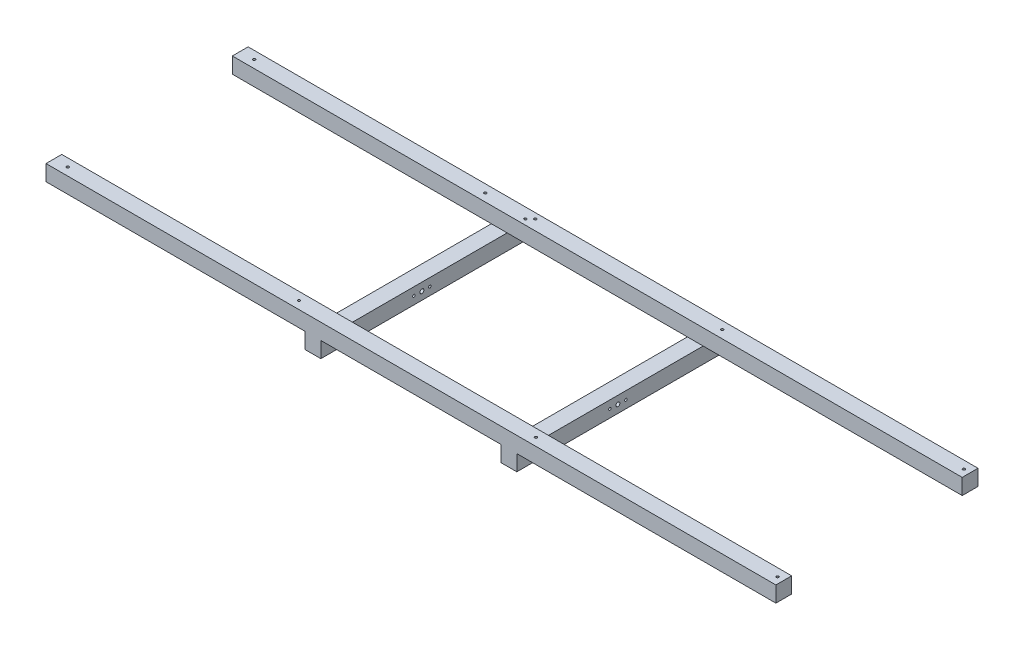
SolidWorks part; units mm, degrees
ref_plane "Plano frontal" through (0, 0, 0) normal (0, 0, 1) x (1, 0, 0)
ref_plane "Plano superior" through (0, 0, 0) normal (0, 1, 0) x (1, 0, 0)
ref_plane "Plano direito" through (0, 0, 0) normal (1, 0, 0) x (0, 0, -1)
sketch "Esboço1" plane through (0, 0, 0) normal (0, 1, 0) x (1, 0, 0)
  line L1 (-212.55, 202.85) -> (-180.85, 202.85)
  line L2 (-212.55, 202.85) -> (-212.55, -202.85)
  line L3 (-212.55, -202.85) -> (-180.85, -202.85)
  line L4 (-180.85, 202.85) -> (-180.85, -202.85)
  line L5 (180.85, 202.85) -> (212.55, 202.85)
  line L6 (180.85, 202.85) -> (180.85, -202.85)
  line L7 (180.85, -202.85) -> (212.55, -202.85)
  line L8 (212.55, 202.85) -> (212.55, -202.85)
  dimension "D1" = 405.7
  dimension "D2" = 31.7
  dimension "D3" = 31.7
  dimension "D4" = 405.7
  dimension "D5" = 361.7
extrude "Ressalto-extrusão1" add sketch "Esboço1" against normal blind 31.7
sketch "Esboço3" plane through (0, 0, 0) normal (0, 1, 0) x (1, 0, 0)
  line L0 (-212.55, 202.85) -> (-212.55, -202.85) construction
  line L1 (-732.55, 202.85) -> (732.55, 202.85)
  line L2 (-732.55, 202.85) -> (-732.55, 171.15)
  line L3 (-732.55, 171.15) -> (732.55, 171.15)
  line L4 (732.55, 202.85) -> (732.55, 171.15)
  line L5 (-732.55, -202.85) -> (732.55, -202.85)
  line L6 (-732.55, -202.85) -> (-732.55, -171.15)
  line L7 (-732.55, -171.15) -> (732.55, -171.15)
  line L8 (732.55, -202.85) -> (732.55, -171.15)
  line L9 (212.55, -202.85) -> (212.55, 202.85) construction
  dimension "D1" = 1465.1
  dimension "D2" = 520
  dimension "D3" = 405.7
  dimension "D4" = 31.7
  dimension "D5" = 31.7
  dimension "D6" = 520
extrude "Ressalto-extrusão2" add sketch "Esboço3" along normal blind 31.7
sketch "Esboço4" plane through (0, 0, 0) normal (0, 1, 0) x (1, 0, 0)
  line L0 (732.55, 171.15) -> (732.55, 202.85) construction
  line L1 (732.55, -202.85) -> (732.55, -171.15) construction
  line L2 (-732.55, -171.15) -> (-732.55, -202.85) construction
  line L3 (-732.55, 202.85) -> (-732.55, 171.15) construction
  line L4 (-732.55, 171.15) -> (732.55, 171.15) construction
  line L5 (732.55, -171.15) -> (-732.55, -171.15) construction
  line L6 (-732.55, -202.85) -> (732.55, -202.85) construction
  line L7 (732.55, 202.85) -> (-732.55, 202.85) construction
  line L8 (-180.85, -171.15) -> (-180.85, 171.15) construction
  circle A0 centre (720, 187) radius 2.5
  circle A1 centre (720, -187) radius 2.5
  circle A2 centre (235.05, 187) radius 2.5
  circle A3 centre (235.05, -187) radius 2.5
  circle A4 centre (-704.55, 187) radius 2.5
  circle A5 centre (-704.55, -187) radius 2.5
  circle A6 centre (-240.55, 187) radius 2.5
  circle A7 centre (-240.55, -187) radius 2.5
  circle A10 centre (-155, 182) radius 2.5
  circle A11 centre (-145, 192) radius 2.5
  point P24 (0, 0)
  point P26 (-155.2024, 184.0108)
  dimension "D1" = 5
  dimension "D6" = 5
  dimension "D15" = 10
  dimension "D19" = 5
  dimension "D2" = 12.55
  dimension "D3" = 484.95
  dimension "D4" = 12.55
  dimension "D5" = 484.95
  dimension "D7" = 28
  dimension "D8" = 464
  dimension "D9" = 28
  dimension "D10" = 464
  dimension "D11" = 15.85
  dimension "D12" = 15.85
  dimension "D13" = 15.85
  dimension "D14" = 15.85
  dimension "D16" = 10
  dimension "D17" = 10.85
  dimension "D18" = 25.85
extrude "Corte-extrusão2" cut sketch "Esboço4" along normal blind 31.7
sketch "Esboço5" plane through (0, 0, 0) normal (1, 0, 0) x (0, 0, -1)
  line L0 (-171.15, 0) -> (171.15, 0) construction
  line L1 (-202.85, -31.7) -> (-202.85, 0) construction
  circle A0 centre (16, -15.85) radius 2.5
  circle A1 centre (-16, -15.85) radius 2.5
  circle A2 centre (0, -15.85) radius 4
  dimension "D1" = 8
  dimension "D2" = 5
  dimension "D3" = 5
  dimension "D4" = 15.85
  dimension "D5" = 202.85
  dimension "D6" = 32
  dimension "D7" = 16
extrude "Corte-extrusão3" cut sketch "Esboço5" against normal through all both and the other way through all
